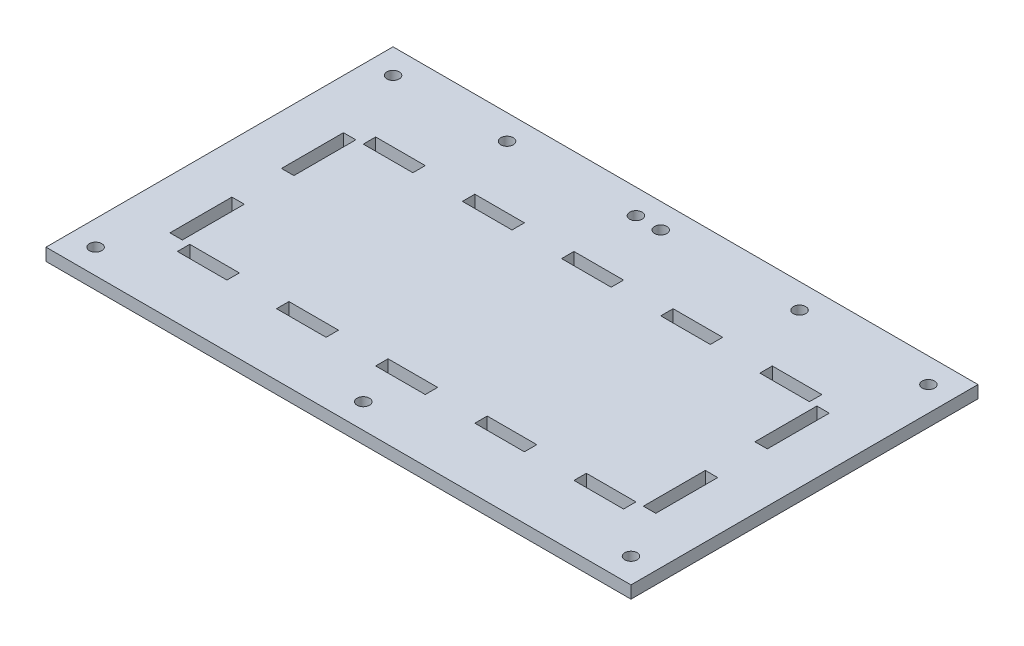
SolidWorks part; units mm, degrees
material "아크릴(내충격성)"
ref_plane "정면" through (0, 0, 0) normal (0, 0, 1) x (1, 0, 0)
ref_plane "윗면" through (0, 0, 0) normal (0, 1, 0) x (1, 0, 0)
ref_plane "우측면" through (0, 0, 0) normal (1, 0, 0) x (0, 0, -1)
sketch "스케치1" plane through (0, 0, 0) normal (0, 1, 0) x (1, 0, 0)
  line L1 (-118, 70) -> (118, 70)
  line L2 (-118, 70) -> (-118, -70)
  line L3 (-118, -70) -> (118, -70)
  line L4 (118, 70) -> (118, -70)
  line L5 (-118, 70) -> (118, -70) construction
  line L6 (-118, -70) -> (118, 70) construction
  point P0 (0, 0)
  dimension "D1" = 140
  dimension "D2" = 236
extrude "보스-돌출1" add sketch "스케치1" along normal blind 5
sketch "스케치2" plane through (0, 5, 0) normal (0, 1, 0) x (1, 0, 0)
  line L0 (-118, -70) -> (118, -70) construction
  line L1 (-10, -45) -> (10, -45)
  line L2 (-10, -45) -> (-10, -40)
  line L3 (-10, -40) -> (10, -40)
  line L4 (10, -45) -> (10, -40)
  line L5 (0, -18.0062) -> (0, -61.9938) construction
  point P9 (0, -40)
  dimension "D1" = 5
  dimension "D2" = 20
  dimension "D3" = 25
extrude "컷-돌출1" cut sketch "스케치2" against normal up to next
pattern_linear "선형 패턴1" count 3 spacing 40 along (1, 0, 0) of "컷-돌출1"
pattern_linear "선형 패턴2" count 3 spacing 40 along (-1, 0, 0) of "컷-돌출1"
sketch "스케치3" plane through (0, 5, 0) normal (0, 1, 0) x (1, 0, 0)
  line L7 (93, -40) -> (98, -40)
  line L8 (93, -40) -> (93, -15)
  line L9 (93, -15) -> (98, -15)
  line L10 (98, -40) -> (98, -15)
  line L11 (90, -40) -> (70, -40) construction
  dimension "D1" = 25
  dimension "D2" = 5
  dimension "D3" = 93
extrude "컷-돌출2" cut sketch "스케치3" against normal up to next
mirror "대칭 복사3" about plane through (0, 0, 0) normal (1, 0, 0) of "컷-돌출2"
pattern_linear "선형 패턴6" count 2 spacing 75 along (0, 0, -1) of "선형 패턴2", "선형 패턴1", "컷-돌출1"
pattern_linear "선형 패턴7" count 2 spacing 45 along (0, 0, -1) of "대칭 복사3", "컷-돌출2"
sketch "스케치4" plane through (0, 5, 0) normal (0, 1, 0) x (1, 0, 0)
  line L0 (-118, 50) -> (-98, 70) construction
  line L6 (-118, 70) -> (-98, 70)
  line L8 (-118, 70) -> (-118, 50)
  line L11 (-118, 50) -> (-98, 50)
  line L12 (-98, 70) -> (-98, 50)
  line L13 (-118, -70) -> (-98, -70)
  line L14 (-118, -70) -> (-118, -50)
  line L15 (-118, -50) -> (-98, -50)
  line L16 (-98, -70) -> (-98, -50)
  line L17 (118, 70) -> (98, 70)
  line L18 (118, 70) -> (118, 50)
  line L19 (118, 50) -> (98, 50)
  line L20 (98, 70) -> (98, 50)
  line L21 (118, -70) -> (98, -70)
  line L22 (118, -70) -> (118, -50)
  line L23 (118, -50) -> (98, -50)
  line L24 (98, -70) -> (98, -50)
  line L25 (98, -70) -> (118, -50) construction
  circle A0 centre (-108, 60) radius 2.5
  circle A1 centre (108, -60) radius 2.5
  circle A2 centre (-108, -60) radius 2.5
  circle A3 centre (108, 60) radius 2.5
  circle A4 centre (0, 60) radius 2.5
  circle A6 centre (0, -60) radius 2.5
  circle A7 centre (-62, 60) radius 2.5
  circle A8 centre (56, 60) radius 2.5
  circle A9 centre (-10, 60) radius 2.5
  dimension "D5" = 5
  dimension "D6" = 5
  dimension "D7" = 5
  dimension "D8" = 5
  dimension "D9" = 52
  dimension "D10" = 52
  dimension "D11" = 10
  dimension "D13" = 5
  dimension "D14" = 5
  dimension "D15" = 5
  dimension "D16" = 5
  dimension "D1" = 20
  dimension "D2" = 20
  dimension "D3" = 20
  dimension "D4" = 20
  dimension "D12" = 170
extrude "컷-돌출3" cut sketch "스케치4" against normal blind 10 contours A2 | A0 | A3 | A1 | A4 | A6 | A7 | A9 | A8
